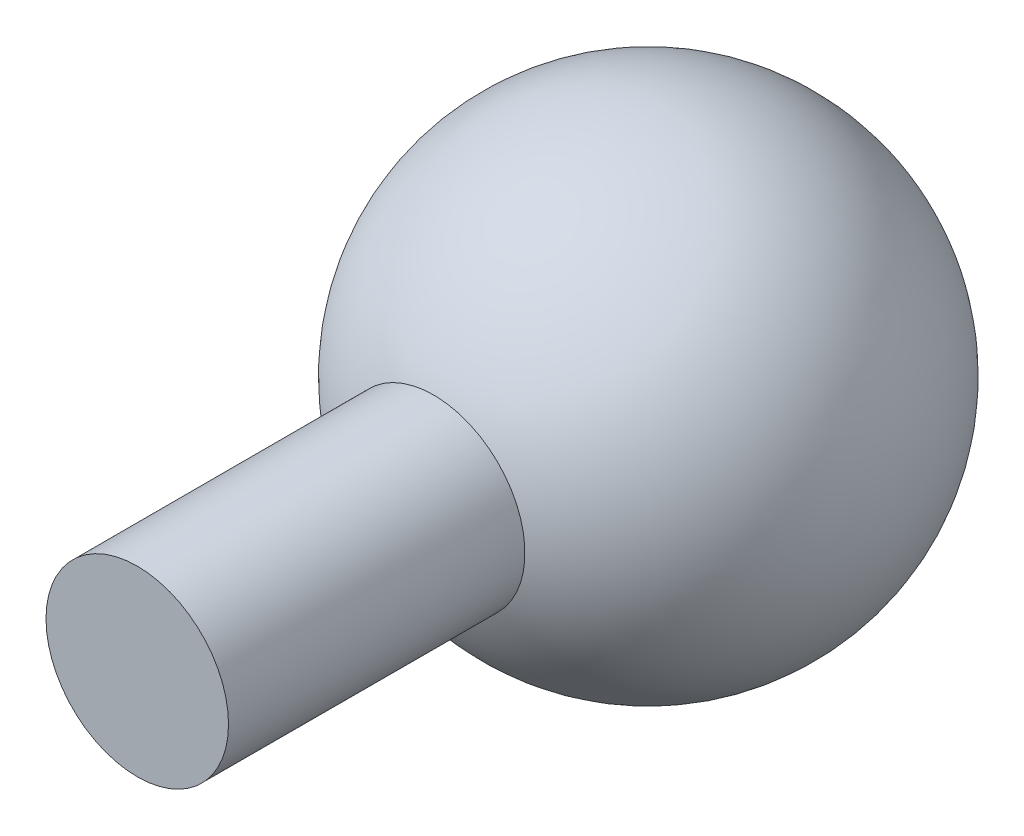
SolidWorks part; units mm, degrees
ref_plane "Plan de face" through (0, 0, 0) normal (0, 0, 1) x (1, 0, 0)
ref_plane "Plan de dessus" through (0, 0, 0) normal (0, 1, 0) x (1, 0, 0)
ref_plane "Plan de droite" through (0, 0, 0) normal (1, 0, 0) x (0, 0, -1)
sketch "Esquisse1" plane through (0, 0, 0) normal (0, 0, 1) x (1, 0, 0)
  line L0 (0, 0) -> (0, 9.6765) construction
  line L1 (0, 6.3899) -> (0, -6.3899)
  arc A0 (0, 6.3899) -> (0, -6.3899) centre (0, 0) ccw
revolve "Révolution3" add sketch "Esquisse1" angle 360 about L0
sketch "Esquisse2" plane through (0, 0, 0) normal (0, 0, 1) x (1, 0, 0)
  circle A0 centre (0, 0) radius 2.5
  dimension "D1" = 5
extrude "Boss.-Extru.1" add sketch "Esquisse2" along normal blind 14
